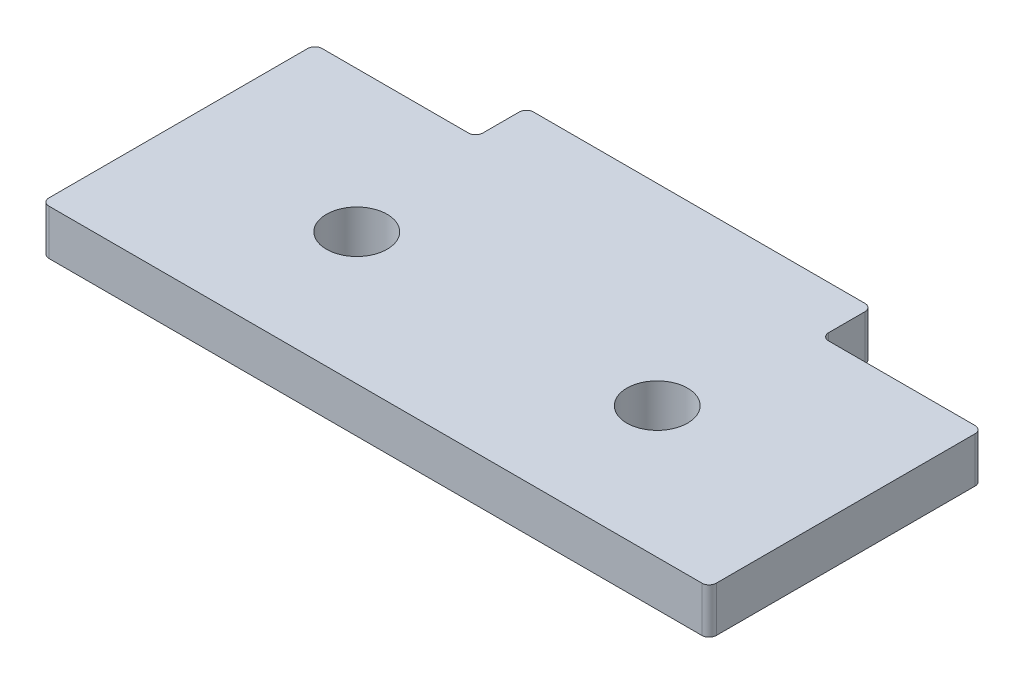
SolidWorks part; units mm, degrees
material "Plain Carbon Steel"
ref_plane "Front Plane" through (0, 0, 0) normal (0, 0, 1) x (1, 0, 0)
ref_plane "Top Plane" through (0, 0, 0) normal (0, 1, 0) x (1, 0, 0)
ref_plane "Right Plane" through (0, 0, 0) normal (1, 0, 0) x (0, 0, -1)
sketch "Sketch2" plane through (0, 0, 0) normal (0, 1, 0) x (1, 0, 0)
  line L0 (47, -22.9607) -> (47, 15.8607) construction
  line L1 (47, 15.8607) -> (24.5, 15.8607) construction
  line L2 (24.5, 15.8607) -> (24.5, 22.9607) construction
  line L3 (24.5, 22.9607) -> (-24.5, 22.9607) construction
  line L4 (-24.5, 22.9607) -> (-24.5, 15.8607) construction
  line L5 (-24.5, 15.8607) -> (-47, 15.8607) construction
  line L6 (-47, 15.8607) -> (-47, -22.9607) construction
  line L7 (-47, -22.9607) -> (47, -22.9607) construction
  line L8 (0, 22.9607) -> (0, -22.9607) construction
  line L9 (0, 0) -> (47, 0) construction
  line L10 (46.7, -22.6607) -> (46.7, 15.5607)
  line L11 (46.7, 15.5607) -> (24.2, 15.5607)
  line L12 (24.2, 15.5607) -> (24.2, 22.6607)
  line L13 (24.2, 22.6607) -> (-24.2, 22.6607)
  line L14 (-24.2, 22.6607) -> (-24.2, 15.5607)
  line L15 (-24.2, 15.5607) -> (-46.7, 15.5607)
  line L16 (-46.7, 15.5607) -> (-46.7, -22.6607)
  line L17 (-46.7, -22.6607) -> (46.7, -22.6607)
  dimension "D1" = 7.1
  dimension "D2" = 38.8214
  dimension "D3" = 49
  dimension "D4" = 94
  dimension "D5" = 49
  dimension "D6" = 0.3
extrude "Boss-Extrude2" add sketch "Sketch2" along normal blind 6.35
sketch "Sketch3" plane through (0, 6.35, 0) normal (0, 1, 0) x (1, 0, 0)
  line L0 (-46.7, 15.5607) -> (-46.7, -22.6607) construction
  line L1 (-46.7, -22.6607) -> (46.7, -22.6607) construction
  circle A0 centre (-21.05, -4.2252) radius 4.25
  circle A1 centre (21.05, -4.2752) radius 4.25
  dimension "D1" = 8.5
  dimension "D2" = 25.65
  dimension "D3" = 18.4354
extrude "Cut-Extrude1" cut sketch "Sketch3" against normal through all
fillet "Fillet1" radius 1 8 edges at (24.2, 3.175, -22.6607) (24.2, 3.175, -15.5607) (46.7, 3.175, -15.5607) (46.7, 3.175, 22.6607) (-46.7, 3.175, 22.6607) (-24.2, 3.175, -22.6607) (-24.2, 3.175, -15.5607) (-46.7, 3.175, -15.5607)
